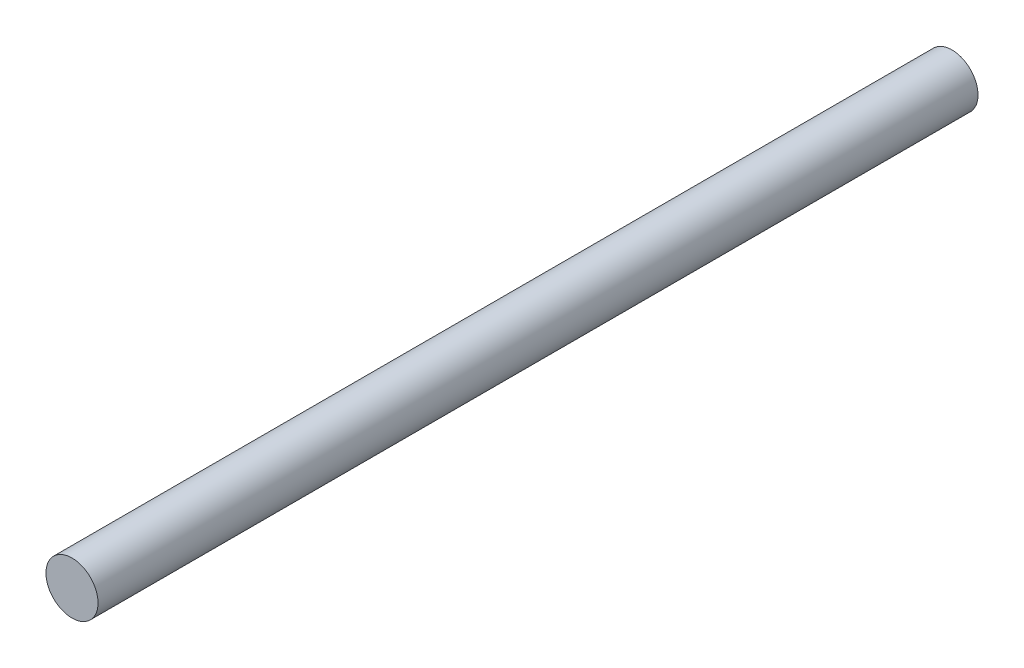
SolidWorks part; units mm, degrees
ref_plane "Front Plane" through (0, 0, 0) normal (0, 0, 1) x (1, 0, 0)
ref_plane "Top Plane" through (0, 0, 0) normal (0, 1, 0) x (1, 0, 0)
ref_plane "Right Plane" through (0, 0, 0) normal (1, 0, 0) x (0, 0, -1)
sketch "Sketch1" plane through (0, 0, 0) normal (0, 0, 1) x (1, 0, 0)
  circle A0 centre (0, 0) radius 5
  dimension "D1" = 10
extrude "Boss-Extrude1" add sketch "Sketch1" along normal blind 169
